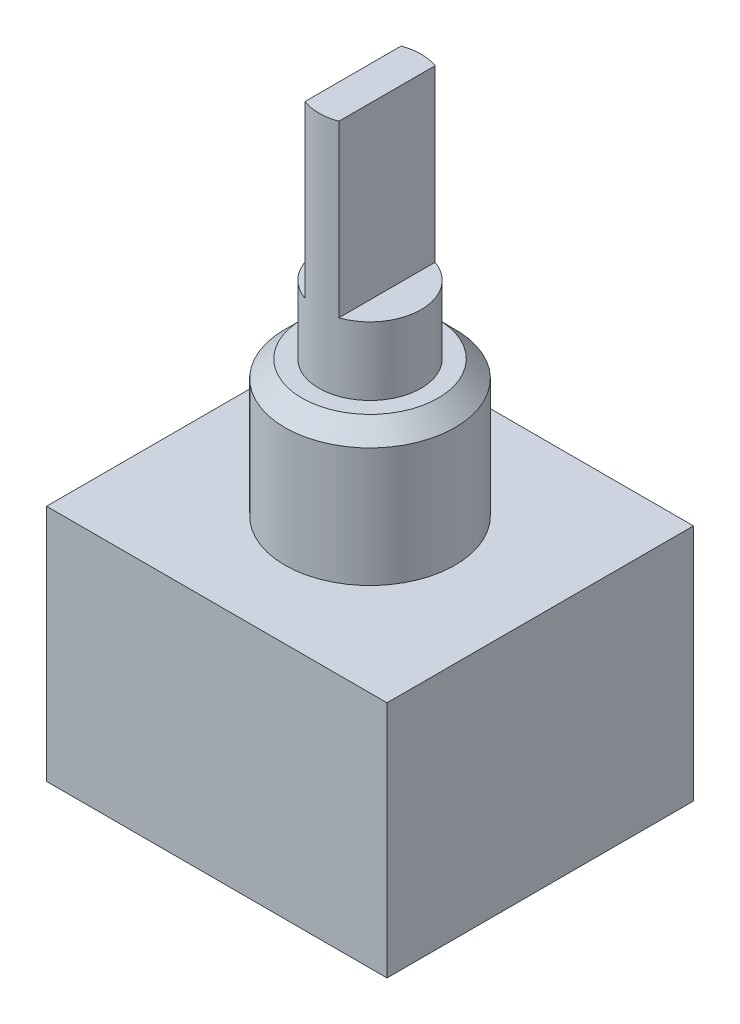
SolidWorks part; units mm, degrees
ref_plane "前视基准面" through (0, 0, 0) normal (0, 0, 1) x (1, 0, 0)
ref_plane "上视基准面" through (0, 0, 0) normal (0, 1, 0) x (1, 0, 0)
ref_plane "右视基准面" through (0, 0, 0) normal (1, 0, 0) x (0, 0, -1)
other "Configuration Table"
sketch "草图1" plane through (0, 0, 0) normal (0, 1, 0) x (1, 0, 0)
  line L1 (-5, -4.5) -> (5, -4.5)
  line L2 (-5, -4.5) -> (-5, 4.5)
  line L3 (-5, 4.5) -> (5, 4.5)
  line L4 (5, -4.5) -> (5, 4.5)
  line L5 (-5, -4.5) -> (5, 4.5) construction
  line L6 (-5, 4.5) -> (5, -4.5) construction
  point P0 (0, 0)
  dimension "D1" = 10
  dimension "D2" = 9
extrude "凸台-拉伸1" add sketch "草图1" along normal blind 7
sketch "草图2" plane through (0, 7, 0) normal (0, 1, 0) x (1, 0, 0)
  circle A0 centre (0, 0) radius 2.5
  dimension "D1" = 5
extrude "凸台-拉伸2" add sketch "草图2" along normal blind 4
chamfer "倒角1" distance 0.5 angle 45 1 edges at (0, 11, 2.5)
sketch "草图3" plane through (0, 11, 0) normal (0, 1, 0) x (1, 0, 0)
  circle A0 centre (0, 0) radius 1.5
  dimension "D1" = 3
extrude "凸台-拉伸3" add sketch "草图3" along normal blind 7
sketch "草图4" plane through (0, 18, 0) normal (0, 1, 0) x (1, 0, 0)
  line L0 (-0.5, 1.4142) -> (-0.5, -1.4142)
  line L1 (0, 0) -> (0, 50000) construction
  line L2 (0.5, 1.4142) -> (0.5, -1.4142)
  circle A0 centre (0, 0) radius 1.5 construction
  circle A1 centre (0, 0) radius 1.5 construction
  arc A2 (-0.5, 1.4142) -> (-0.5, -1.4142) centre (0, 0) ccw
  arc A3 (0.5, 1.4142) -> (0.5, -1.4142) centre (0, 0) cw
  dimension "D1" = 1
extrude "切除-拉伸1" cut sketch "草图4" against normal blind 5
